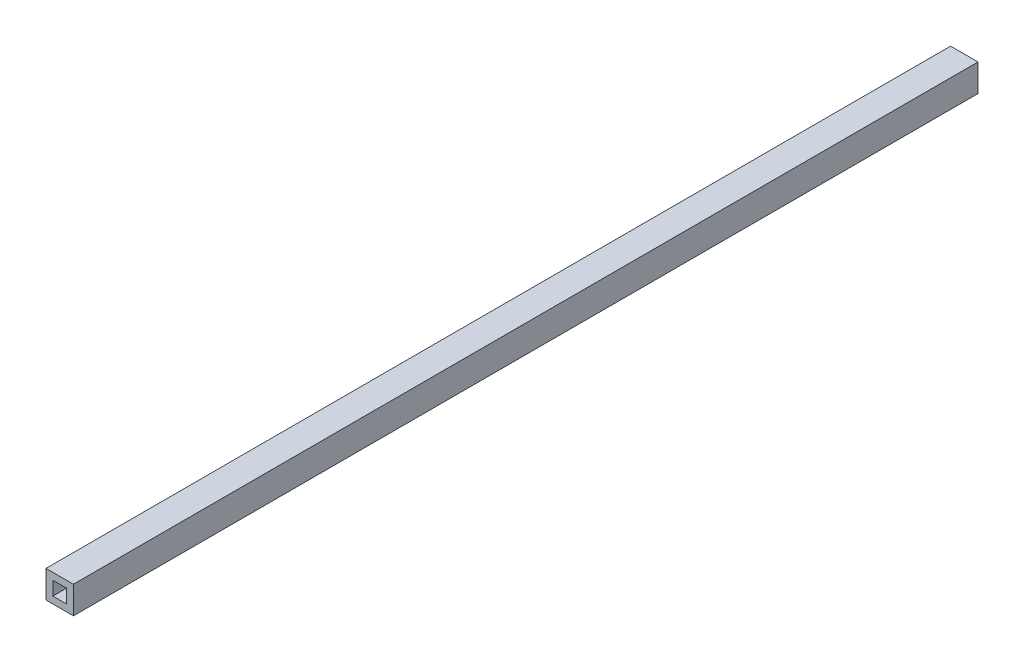
SolidWorks part; units mm, degrees
material "6063-O"
ref_plane "Front Plane" through (0, 0, 0) normal (0, 0, 1) x (1, 0, 0)
ref_plane "Top Plane" through (0, 0, 0) normal (0, 1, 0) x (1, 0, 0)
ref_plane "Right Plane" through (0, 0, 0) normal (1, 0, 0) x (0, 0, -1)
sketch "Sketch1" plane through (0, 0, 0) normal (0, 0, 1) x (1, 0, 0)
  line L1 (-10, -10) -> (10, -10)
  line L2 (-10, -10) -> (-10, 10)
  line L3 (-10, 10) -> (10, 10)
  line L4 (10, -10) -> (10, 10)
  line L5 (-10, -10) -> (10, 10) construction
  line L6 (-10, 10) -> (10, -10) construction
  point P0 (0, 0)
  dimension "D1" = 20
extrude "Extrude-Thin1" add sketch "Sketch1" along normal blind 660 thin thin type one direction reverse wall 5
